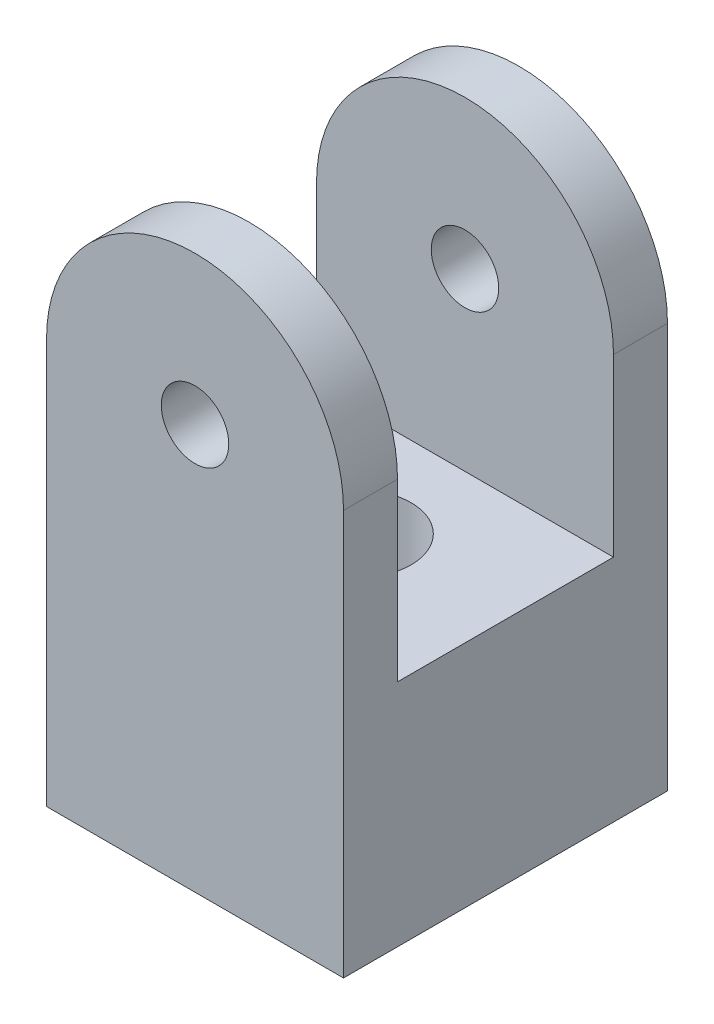
SolidWorks part; units mm, degrees
ref_plane "Alzado" through (0, 0, 0) normal (0, 0, 1) x (1, 0, 0)
ref_plane "Planta" through (0, 0, 0) normal (0, 1, 0) x (1, 0, 0)
ref_plane "Vista lateral" through (0, 0, 0) normal (1, 0, 0) x (0, 0, -1)
sketch "Croquis1" plane through (0, 0, 0) normal (0, 1, 0) x (1, 0, 0)
  line L1 (-11, -12) -> (11, -12)
  line L2 (-11, -12) -> (-11, 12)
  line L3 (-11, 12) -> (11, 12)
  line L4 (11, -12) -> (11, 12)
  line L5 (-11, -12) -> (11, 12) construction
  line L6 (-11, 12) -> (11, -12) construction
  point P0 (0, 0)
  dimension "D1" = 24
  dimension "D2" = 22
extrude "Saliente-Extruir1" add sketch "Croquis1" along normal blind 30
sketch "Croquis3" plane through (0, 0, 12) normal (0, 0, 1) x (1, 0, 0)
  line L1 (-11, 30) -> (11, 30) construction
  line L2 (-11, 30) -> (11, 30)
  arc A0 (11, 30) -> (-11, 30) centre (0, 30) ccw
extrude "Saliente-Extruir2" add sketch "Croquis3" against normal blind 24
sketch "Croquis4" plane through (11, 0, 0) normal (1, 0, 0) x (0, 0, -1)
  line L0 (-8, 0) -> (-8, 17) construction
  line L1 (-12, 0) -> (12, 0) construction
  line L2 (-8, 17) -> (8, 17)
  line L3 (-12, 30) -> (-12, 0) construction
  line L5 (-8, 17) -> (-8, 44.5519)
  line L6 (-8, 44.5519) -> (8, 44.5519)
  line L7 (8, 44.5519) -> (8, 17)
  dimension "D1" = 17
  dimension "D2" = 4
  dimension "D3" = 16
extrude "Cortar-Extruir1" cut sketch "Croquis4" against normal blind 24
sketch "Croquis5" plane through (0, 17, 0) normal (0, 1, 0) x (1, 0, 0)
  circle A0 centre (0, 0) radius 4
  dimension "D1" = 8
extrude "Cortar-Extruir2" cut sketch "Croquis5" against normal blind 24
sketch "Croquis6" plane through (0, 0, 12) normal (0, 0, 1) x (1, 0, 0)
  circle A0 centre (0, 30) radius 2.5
  dimension "D1" = 5
extrude "Cortar-Extruir3" cut sketch "Croquis6" against normal through all
